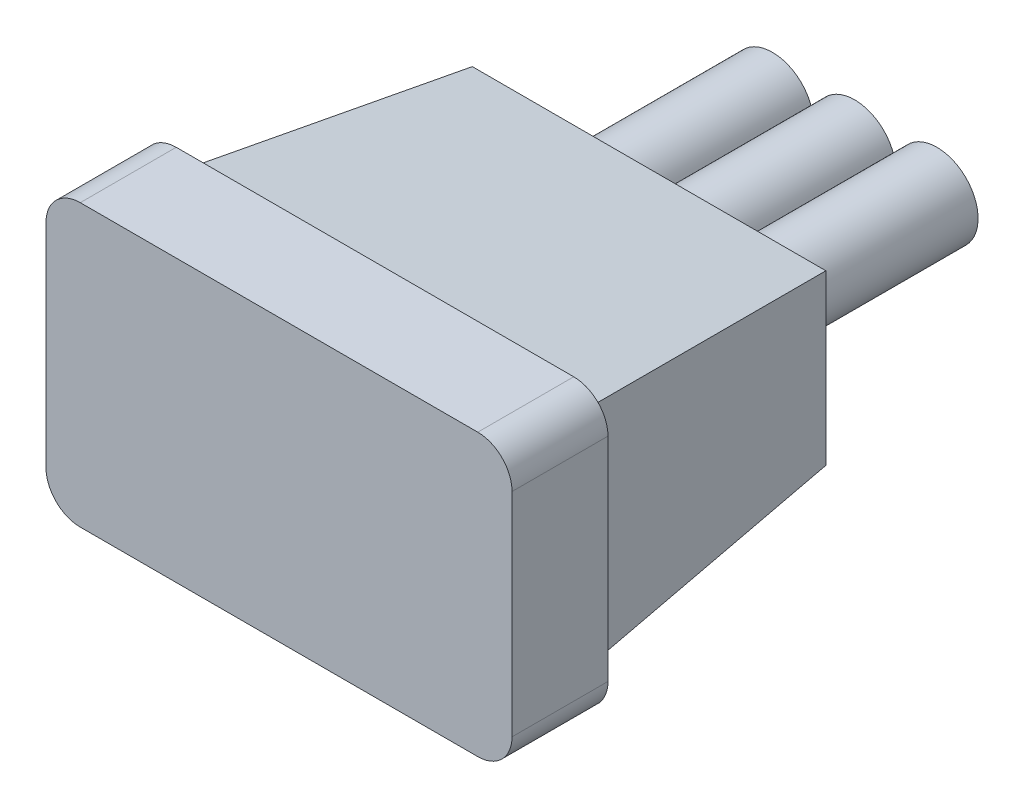
SolidWorks part; units mm, degrees
ref_plane "Front Plane" through (0, 0, 0) normal (0, 0, 1) x (1, 0, 0)
ref_plane "Top Plane" through (0, 0, 0) normal (0, 1, 0) x (1, 0, 0)
ref_plane "Right Plane" through (0, 0, 0) normal (1, 0, 0) x (0, 0, -1)
sketch "Sketch1" plane through (0, 0, 0) normal (0, 0, 1) x (1, 0, 0)
  line L1 (-3.4, 2.05) -> (3.4, 2.05)
  line L2 (-3.4, 2.05) -> (-3.4, -2.05)
  line L3 (-3.4, -2.05) -> (3.4, -2.05)
  line L4 (3.4, 2.05) -> (3.4, -2.05)
  line L5 (-3.4, 2.05) -> (3.4, -2.05) construction
  line L6 (-3.4, -2.05) -> (3.4, 2.05) construction
  point P0 (0, 0)
  dimension "D1" = 6.8
  dimension "D2" = 4.1
extrude "Boss-Extrude1" add sketch "Sketch1" against normal blind 1.4
sketch "Sketch2" plane through (0, 0, -1.4) normal (0, 0, -1) x (-1, 0, 0)
  line L1 (3, 1.65) -> (-3, 1.65)
  line L2 (3, 1.65) -> (3, -1.65)
  line L3 (3, -1.65) -> (-3, -1.65)
  line L4 (-3, 1.65) -> (-3, -1.65)
  line L5 (3, 1.65) -> (-3, -1.65) construction
  line L6 (3, -1.65) -> (-3, 1.65) construction
  line L7 (-3.4, 2.05) -> (3.4, 2.05) construction
  line L8 (-3.4, -2.05) -> (-3.4, 2.05) construction
  point P0 (0, 0)
  dimension "D1" = 0.4
  dimension "D2" = 0.4
extrude "Boss-Extrude2" add sketch "Sketch2" along normal blind 4 draft 6
fillet "Fillet1" radius 0.5 4 edges at (-3.4, -2.05, -0.7) (-3.4, 2.05, -0.7) (3.4, -2.05, -0.7) (3.4, 2.05, -0.7)
sketch "Sketch3" plane through (0, 0, -5.4) normal (0, 0, -1) x (-1, 0, 0)
  circle A0 centre (0, 0) radius 0.6
  dimension "D1" = 1.2
extrude "POSITIVE" add sketch "Sketch3" along normal blind 3 separate body
sketch "Sketch4" plane through (0, 0, -5.4) normal (0, 0, -1) x (-1, 0, 0)
  line L0 (1.2, 0) -> (0, 0) construction
  circle A0 centre (1.2, 0) radius 0.6
  circle A1 centre (0, 0) radius 0.6 construction
extrude "SIGNAL" add sketch "Sketch4" along normal up to surface (3 mm away) separate body up to face at (-0.6, 0, -8.4)
sketch "Sketch5" plane through (0, 0, -5.4) normal (0, 0, -1) x (-1, 0, 0)
  line L0 (0, 0) -> (-1.2, 0) construction
  circle A0 centre (-1.2, 0) radius 0.6
  circle A1 centre (0, 0) radius 0.6 construction
extrude "NEGATIVE" add sketch "Sketch5" along normal up to surface (3 mm away) separate body up to face at (-0.6, 0, -8.4)
move or copy body "Body-Move/Copy1" [suppressed] bodies to move or copy 102 103 104 105
move or copy body "Body-Move/Copy2" [suppressed] bodies to move or copy 106 107 108 109
